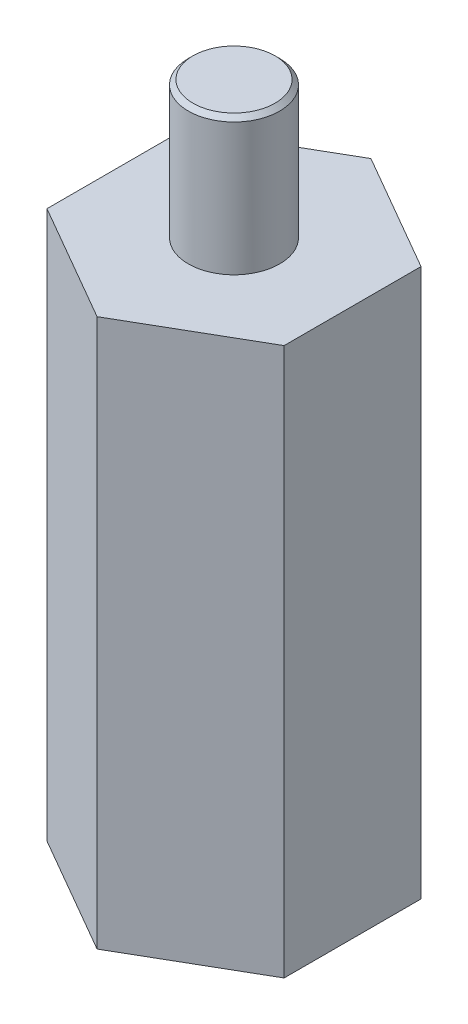
SolidWorks part; units mm, degrees
ref_plane "Спереди" through (0, 0, 0) normal (0, 0, 1) x (1, 0, 0)
ref_plane "Сверху" through (0, 0, 0) normal (0, 1, 0) x (1, 0, 0)
ref_plane "Справа" through (0, 0, 0) normal (1, 0, 0) x (0, 0, -1)
sketch "Эскиз1" plane through (0, 0, 0) normal (0, 1, 0) x (1, 0, 0)
  line L1 (0, 3) -> (-2.5981, 1.5)
  line L2 (-2.5981, 1.5) -> (-2.5981, -1.5)
  line L3 (-2.5981, -1.5) -> (0, -3)
  line L4 (0, -3) -> (2.5981, -1.5)
  line L5 (2.5981, -1.5) -> (2.5981, 1.5)
  line L6 (2.5981, 1.5) -> (0, 3)
  circle A0 centre (0, 0) radius 3 construction
  dimension "D1" = 6
extrude "Бобышка-Вытянуть1" add sketch "Эскиз1" along normal blind 12
sketch "Эскиз2" plane through (0, 12, 0) normal (0, 1, 0) x (1, 0, 0)
  circle A0 centre (0, 0) radius 1
  dimension "D1" = 2
extrude "Бобышка-Вытянуть2" add sketch "Эскиз2" along normal blind 3
hole_wizard "Отверстие обработанное метчиком M2.5x0.451" positions "Трехмерный эскиз2" profile "Эскиз4" tap size "M2.5x0.45" standard "Ansi Metric"
sketch3d "Трехмерный эскиз2"
  point P0 (0, 0, 0)
  point P3 (0, 0, 0)
cosmetic thread "Отверстие резьбы3" parameters "D1"=5, "D2"=2.5
sketch "Эскиз4" plane through (0, 0, 0) normal (1, 0, 0) x (0, 0, -1)
  line L0 (0, 0) -> (0, 10.6159)
  line L1 (0, 10.6159) -> (1.025, 10)
  line L2 (1.025, 10) -> (1.025, 0)
  line L5 (1.025, 0) -> (0, 0)
  line L10 (0, 10.6159) -> (-1.025, 10) construction
  line L11 (0, -6.35) -> (0, 107.95) construction
  dimension "Диаметр сверла" = 2.05
  dimension "Глубина сверла" = 10
  dimension "Угол заточки сверла" = 118
cosmetic thread "Отверстие резьбы4" parameters "D1"=5, "D2"=2.5
chamfer "Фаска1" distance 0.1 angle 45 1 edges at (0, 15, 1)
